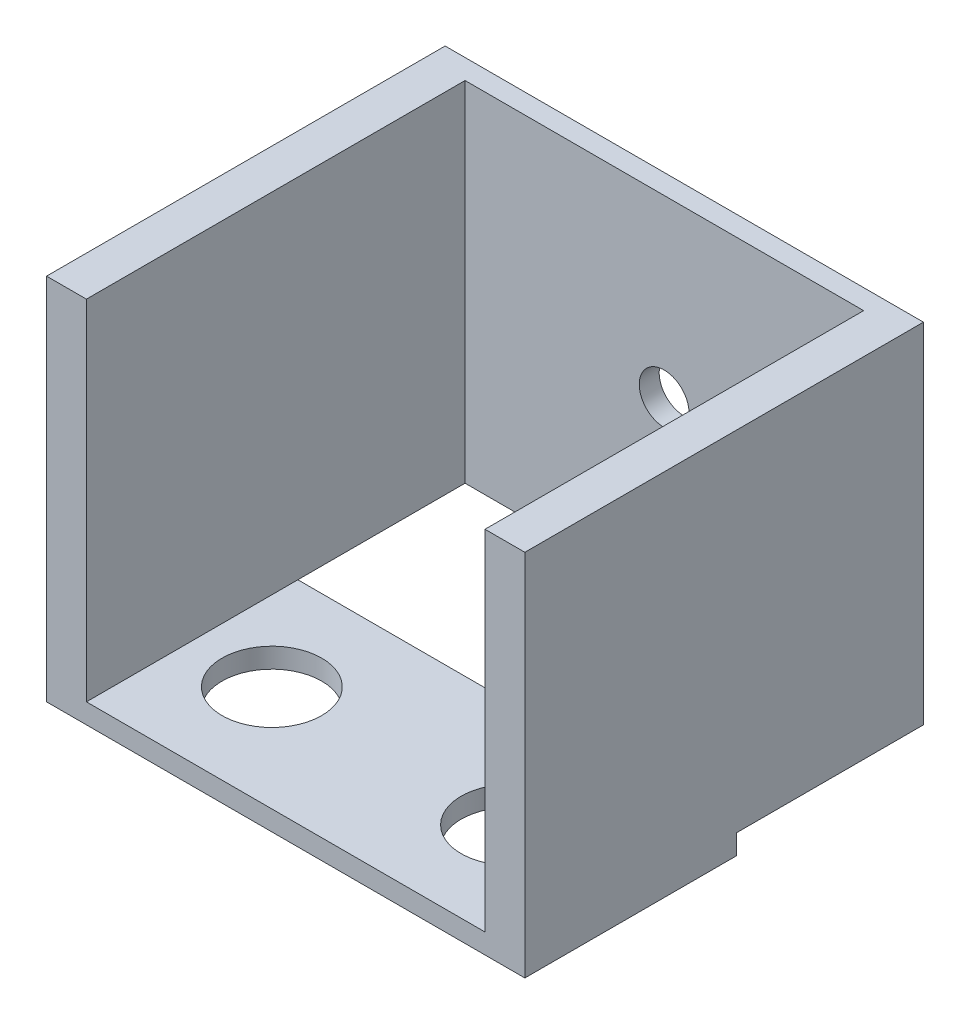
SolidWorks part; units mm, degrees
ref_plane "Plano frontal" through (0, 0, 0) normal (0, 0, 1) x (1, 0, 0)
ref_plane "Plano superior" through (0, 0, 0) normal (0, 1, 0) x (1, 0, 0)
ref_plane "Plano direito" through (0, 0, 0) normal (1, 0, 0) x (0, 0, -1)
sketch "Esboço1" plane through (0, 0, 0) normal (0, 0, 1) x (1, 0, 0)
  line L1 (-51.7922, -3.6714) -> (-3.7922, -3.6714)
  line L2 (-51.7922, -3.6714) -> (-51.7922, -38.6714)
  line L3 (-51.7922, -38.6714) -> (-3.7922, -38.6714)
  line L4 (-3.7922, -3.6714) -> (-3.7922, -38.6714)
  circle A0 centre (-27.8109, -21.3376) radius 2.5
  point P4 (-27.8109, -21.3376)
  point P7 (-27.8109, -21.3376)
  point P8 (-27.7922, -21.1714)
  dimension "D1" = 5
extrude "Ressalto-extrusão1" add sketch "Esboço1" along normal blind 2
sketch "Esboço2" plane through (0, 0, 2) normal (0, 0, 1) x (1, 0, 0)
  line L0 (-51.7922, -38.6714) -> (-3.7922, -38.6714) construction
  line L1 (-51.7922, -3.6714) -> (-47.7922, -3.6714)
  line L2 (-51.7922, -3.6714) -> (-51.7922, -38.6714)
  line L3 (-51.7922, -38.6714) -> (-47.7922, -38.6714)
  line L4 (-47.7922, -3.6714) -> (-47.7922, -38.6714)
  line L6 (-3.7922, -3.6714) -> (-7.7922, -3.6714)
  line L7 (-3.7922, -3.6714) -> (-3.7922, -38.6714)
  line L8 (-3.7922, -38.6714) -> (-7.7922, -38.6714)
  line L9 (-7.7922, -3.6714) -> (-7.7922, -38.6714)
extrude "Ressalto-extrusão2" add sketch "Esboço2" along normal blind 38
sketch "Esboço3" plane through (0, -38.6714, 0) normal (0, -1, 0) x (1, 0, 0)
  line L0 (-3.7922, 40) -> (-3.7922, 0) construction
  line L1 (-51.7922, 40) -> (-3.7922, 40)
  line L2 (-51.7922, 40) -> (-51.7922, 18.7799)
  line L3 (-51.7922, 18.7799) -> (-3.7922, 18.7799)
  line L4 (-3.7922, 40) -> (-3.7922, 18.7799)
  circle A0 centre (-39.7922, 29.39) radius 5
  circle A1 centre (-15.7922, 29.39) radius 5
  dimension "D1" = 12
  dimension "D2" = 12
extrude "Ressalto-extrusão3" add sketch "Esboço3" along normal blind 2
